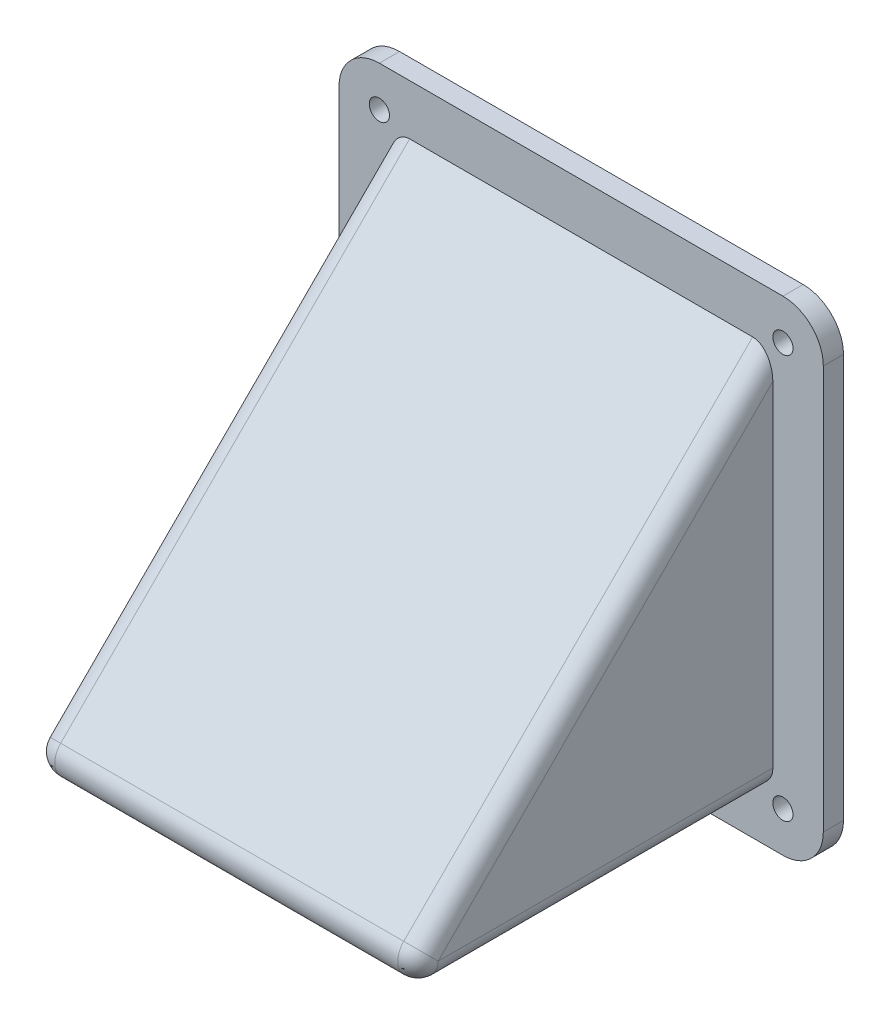
SolidWorks part; units mm, degrees
ref_plane "Front Plane" through (0, 0, 0) normal (0, 0, 1) x (1, 0, 0)
ref_plane "Top Plane" through (0, 0, 0) normal (0, 1, 0) x (1, 0, 0)
ref_plane "Right Plane" through (0, 0, 0) normal (1, 0, 0) x (0, 0, -1)
sketch "Sketch2" plane through (0, 0, 0) normal (0, 0, 1) x (1, 0, 0)
  line L1 (0, 0) -> (120, 0)
  line L2 (0, 0) -> (0, -120)
  line L3 (0, -120) -> (120, -120)
  line L4 (120, 0) -> (120, -120)
  line L5 (16.25, -16.25) -> (103.75, -16.25)
  line L6 (16.25, -16.25) -> (16.25, -103.75)
  line L7 (16.25, -103.75) -> (103.75, -103.75)
  line L8 (103.75, -16.25) -> (103.75, -103.75)
  circle A0 centre (10, -10) radius 2.5
  circle A1 centre (110, -10) radius 2.5
  circle A2 centre (9.989, -110) radius 2.5
  circle A3 centre (109.989, -110) radius 2.5
  dimension "D7" = 5
  dimension "D8" = 5
  dimension "D9" = 5
  dimension "D10" = 5
  dimension "D13" = 10
  dimension "D1" = 120
  dimension "D2" = 120
  dimension "D3" = 100
  dimension "D4" = 100
  dimension "D5" = 100
  dimension "D6" = 100
  dimension "D11" = 10
  dimension "D12" = 10
  dimension "D14" = 87.5
  dimension "D15" = 87.5
  dimension "D16" = 16.25
  dimension "D17" = 16.25
extrude "Boss-Extrude1" add sketch "Sketch2" along normal blind 5
sketch "Sketch3" plane through (0, 0, 5) normal (0, 0, 1) x (1, 0, 0)
  line L8 (12.5, -12.5) -> (12.5, -107.5)
  line L9 (12.5, -107.5) -> (107.5, -107.5)
  line L10 (107.5, -107.5) -> (107.5, -12.5)
  line L11 (107.5, -12.5) -> (12.5, -12.5)
  line L12 (12.5, -12.5) -> (12.5, -107.5)
  line L13 (12.5, -107.5) -> (107.5, -107.5)
  line L14 (107.5, -107.5) -> (107.5, -12.5)
  line L15 (107.5, -12.5) -> (12.5, -12.5)
  dimension "D1" = 12.5
extrude "Boss-Extrude2" add sketch "Sketch3" along normal blind 95 contours L12 L13 L14 L15
sketch "Sketch4" plane through (107.5, 0, 0) normal (1, 0, 0) x (0, 0, -1)
  line L0 (-5, -12.5) -> (-100, -107.5)
  line L1 (-100, -107.5) -> (-100, -12.5)
  line L2 (-100, -12.5) -> (-5, -12.5)
extrude "Cut-Extrude1" cut sketch "Sketch4" against normal blind 95
sketch "Sketch5" plane through (0, -107.5, 0) normal (0, -1, 0) x (1, 0, 0)
  line L0 (12.5, 100) -> (107.5, 100) construction
  line L1 (16.25, 96.25) -> (103.75, 96.25)
  line L2 (16.25, 96.25) -> (16.25, 8.75)
  line L3 (16.25, 8.75) -> (103.75, 8.75)
  line L4 (103.75, 96.25) -> (103.75, 8.75)
  line L5 (12.5, 100) -> (12.5, 5) construction
  dimension "D1" = 87.5
  dimension "D2" = 87.5
  dimension "D3" = 3.75
  dimension "D4" = 3.75
extrude "Cut-Extrude4" cut sketch "Sketch5" against normal offset from surface (0.2145 mm away) 2.5
sketch "Sketch9" plane through (0, 0, 5) normal (0, 0, -1) x (-1, 0, 0)
  line L1 (-103.75, -19.7855) -> (-16.25, -19.7855)
  line L2 (-103.75, -19.7855) -> (-103.75, -103.75)
  line L3 (-103.75, -103.75) -> (-16.25, -103.75)
  line L4 (-16.25, -19.7855) -> (-16.25, -103.75)
extrude "Cut-Extrude5" cut sketch "Sketch9" against normal up to next
sketch "Sketch10" plane through (103.75, 0, 0) normal (-1, 0, 0) x (0, 0, 1)
  line L0 (8.75, -19.7855) -> (5, -19.7855)
  line L1 (5, -19.7855) -> (5, -16.25)
  line L2 (5, -16.25) -> (8.75, -19.7855)
extrude "Cut-Extrude7" cut sketch "Sketch10" along normal blind 87.5
sketch "Sketch11" plane through (0, 0, 8.75) normal (0, 0, 1) x (1, 0, 0)
  line L1 (16.25, -103.75) -> (103.75, -103.75)
  line L2 (16.25, -103.75) -> (16.25, -107.5)
  line L3 (16.25, -107.5) -> (103.75, -107.5)
  line L4 (103.75, -103.75) -> (103.75, -107.5)
extrude "Boss-Extrude3" add sketch "Sketch11" along normal up to next
fillet "Fillet1" radius 10 4 edges at (120, -120, 2.5) (120, 0, 2.5) (0, 0, 2.5) (0, -120, 2.5)
fillet "Fillet2" radius 5 5 edges at (60, -107.5, 100) (12.5, -107.5, 52.5) (12.5, -60, 52.5) (107.5, -107.5, 52.5) (107.5, -60, 52.5)
sketch "Sketch16" plane through (0, -107.5, 0) normal (0, -1, 0) x (1, 0, 0)
  line L0 (102.5, 87.9289) -> (17.5, 87.9289) construction
  line L2 (17.5, 5) -> (102.5, 5) construction
  line L3 (17.5, 87.9289) -> (17.5, 5) construction
  line L4 (20, 82.9289) -> (20, 12.5)
  line L6 (25, 12.5) -> (25, 82.9289)
  line L7 (27.5, 82.9289) -> (27.5, 12.5)
  line L8 (32.5, 12.5) -> (32.5, 82.9289)
  line L9 (35, 82.9289) -> (35, 12.5)
  line L10 (40, 12.5) -> (40, 82.9289)
  line L11 (42.5, 82.9289) -> (42.5, 12.5)
  line L12 (47.5, 12.5) -> (47.5, 82.9289)
  line L13 (50, 82.9289) -> (50, 12.5)
  line L14 (55, 12.5) -> (55, 82.9289)
  line L15 (57.5, 82.9289) -> (57.5, 12.5)
  line L16 (62.5, 12.5) -> (62.5, 82.9289)
  line L17 (65, 82.9289) -> (65, 12.5)
  line L18 (70, 12.5) -> (70, 82.9289)
  line L19 (72.5, 82.9289) -> (72.5, 12.5)
  line L20 (77.5, 12.5) -> (77.5, 82.9289)
  line L21 (80, 82.9289) -> (80, 12.5)
  line L22 (85, 12.5) -> (85, 82.9289)
  line L23 (87.5, 82.9289) -> (87.5, 12.5)
  line L24 (92.5, 12.5) -> (92.5, 82.9289)
  line L25 (95, 82.9289) -> (95, 12.5)
  line L26 (100, 12.5) -> (100, 82.9289)
  arc A91 (25, 82.9289) -> (20, 82.9289) centre (22.5, 82.9289) ccw
  arc A92 (20, 12.5) -> (25, 12.5) centre (22.5, 12.5) ccw
  arc A93 (27.5, 12.5) -> (32.5, 12.5) centre (30, 12.5) ccw
  arc A94 (32.5, 82.9289) -> (27.5, 82.9289) centre (30, 82.9289) ccw
  arc A95 (35, 12.5) -> (40, 12.5) centre (37.5, 12.5) ccw
  arc A96 (40, 82.9289) -> (35, 82.9289) centre (37.5, 82.9289) ccw
  arc A97 (42.5, 12.5) -> (47.5, 12.5) centre (45, 12.5) ccw
  arc A98 (47.5, 82.9289) -> (42.5, 82.9289) centre (45, 82.9289) ccw
  arc A99 (50, 12.5) -> (55, 12.5) centre (52.5, 12.5) ccw
  arc A100 (55, 82.9289) -> (50, 82.9289) centre (52.5, 82.9289) ccw
  arc A101 (57.5, 12.5) -> (62.5, 12.5) centre (60, 12.5) ccw
  arc A102 (62.5, 82.9289) -> (57.5, 82.9289) centre (60, 82.9289) ccw
  arc A103 (65, 12.5) -> (70, 12.5) centre (67.5, 12.5) ccw
  arc A104 (70, 82.9289) -> (65, 82.9289) centre (67.5, 82.9289) ccw
  arc A105 (72.5, 12.5) -> (77.5, 12.5) centre (75, 12.5) ccw
  arc A106 (77.5, 82.9289) -> (72.5, 82.9289) centre (75, 82.9289) ccw
  arc A107 (80, 12.5) -> (85, 12.5) centre (82.5, 12.5) ccw
  arc A108 (85, 82.9289) -> (80, 82.9289) centre (82.5, 82.9289) ccw
  arc A109 (87.5, 12.5) -> (92.5, 12.5) centre (90, 12.5) ccw
  arc A110 (92.5, 82.9289) -> (87.5, 82.9289) centre (90, 82.9289) ccw
  arc A111 (95, 12.5) -> (100, 12.5) centre (97.5, 12.5) ccw
  arc A112 (100, 82.9289) -> (95, 82.9289) centre (97.5, 82.9289) ccw
  dimension "D1" = 5
  dimension "D2" = 5
  dimension "D5" = 5
  dimension "D6" = 5
  dimension "D7" = 11
  dimension "D4" = 7.5
  dimension "D3" = 5
extrude "Cut-Extrude9" cut sketch "Sketch16" against normal blind 5.5
